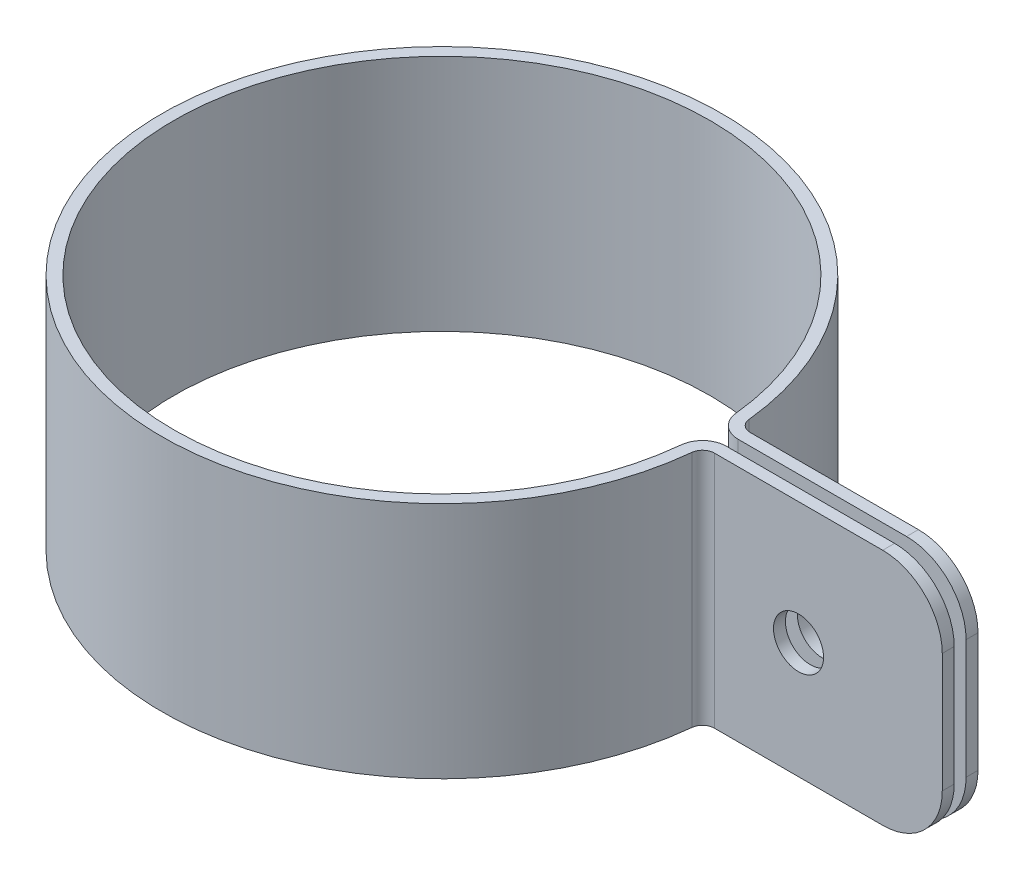
SolidWorks part; units mm, degrees
material "Сталь 20 ГОСТ 1050-88"
ref_plane "Спереди" through (0, 0, 0) normal (0, 0, 1) x (1, 0, 0)
ref_plane "Сверху" through (0, 0, 0) normal (0, 1, 0) x (1, 0, 0)
ref_plane "Справа" through (0, 0, 0) normal (1, 0, 0) x (0, 0, -1)
sketch "Эскиз1" plane through (0, 0, 0) normal (0, 1, 0) x (1, 0, 0)
  line L7 (43.5, -1.5) -> (23.4521, -1.5)
  line L8 (43.5, -0.5) -> (22.4944, -0.5)
  line L9 (43.5, 0.5) -> (22.4944, 0.5)
  line L11 (43.5, 1.5) -> (23.4521, 1.5)
  line L12 (43.5, -1.5) -> (43.5, -0.5)
  line L13 (43.5, 0.5) -> (43.5, 1.5)
  arc A0 (22.4944, 0.5) -> (22.4944, -0.5) centre (0, 0) ccw
  arc A1 (23.4521, 1.5) -> (23.4521, -1.5) centre (0, 0) ccw
  dimension "D1" = 45
  dimension "D2" = 47
extrude "Бобышка-Вытянуть1" add sketch "Эскиз1" along normal blind 20
fillet "Скругление1" radius 2 2 edges at (22.4944, 10, -0.5) (22.4944, 10, 0.5)
fillet "Скругление2" radius 1 2 edges at (23.4521, 10, -1.5) (23.4521, 10, 1.5)
fillet "Скругление3" radius 5 4 edges at (43.5, 0, -1) (43.5, 20, -1) (43.5, 0, 1) (43.5, 20, 1)
hole_wizard "Отверстие обработанное метчиком M51" positions "Эскиз2" profile "Эскиз3" tap size "M5" standard "ISO"
sketch "Эскиз2" plane through (0, 0, -1.5) normal (0, 0, -1) x (-1, 0, 0)
  point P0 (-31.4361, 9.7377)
sketch "Эскиз3" plane through (31.4361, 9.7377, -1.5) normal (1, 0, 0) x (0, 1, 0)
  line L0 (0, 0) -> (0, 39.7618)
  line L1 (0, 39.7618) -> (2.1, 38.5)
  line L2 (2.1, 38.5) -> (2.1, 0)
  line L5 (2.1, 0) -> (0, 0)
  line L10 (0, 39.7618) -> (-2.1, 38.5) construction
  line L11 (0, -6.35) -> (0, 107.95) construction
  dimension "Диаметр сверла" = 4.2
  dimension "Глубина сверла" = 38.5
  dimension "Угол заточки сверла" = 118
cosmetic thread "Отверстие резьбы1" parameters "D1"=3, "D2"=5
